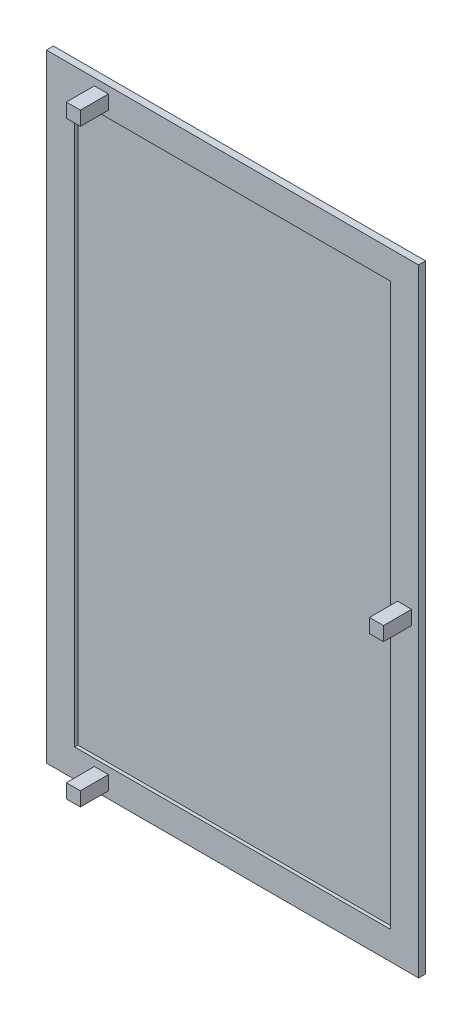
SolidWorks part; units mm, degrees
ref_plane "Front Plane" through (0, 0, 0) normal (0, 0, 1) x (1, 0, 0)
ref_plane "Top Plane" through (0, 0, 0) normal (0, 1, 0) x (1, 0, 0)
ref_plane "Right Plane" through (0, 0, 0) normal (1, 0, 0) x (0, 0, -1)
sketch "Sketch1" plane through (0, 0, 0) normal (0, 0, 1) x (1, 0, 0)
  line L1 (0, 0) -> (66.3, 0)
  line L2 (0, 0) -> (0, 110)
  line L3 (0, 110) -> (66.3, 110)
  line L4 (66.3, 0) -> (66.3, 110)
  dimension "D1" = 110
  dimension "D2" = 66.3
extrude "Boss-Extrude1" add sketch "Sketch1" along normal blind 1.25
sketch "Sketch2" plane through (0, 0, 1.25) normal (0, 0, 1) x (1, 0, 0)
  line L0 (0, 0) -> (66.3, 0) construction
  line L1 (8.55, 1.25) -> (11.05, 1.25)
  line L2 (8.55, 1.25) -> (8.55, 3.75)
  line L3 (8.55, 3.75) -> (11.05, 3.75)
  line L4 (11.05, 1.25) -> (11.05, 3.75)
  line L5 (66.3, 0) -> (66.3, 110) construction
  line L6 (66.3, 110) -> (0, 110) construction
  line L7 (8.55, 108.75) -> (11.05, 108.75)
  line L8 (8.55, 108.75) -> (8.55, 106.25)
  line L9 (8.55, 106.25) -> (11.05, 106.25)
  line L10 (11.05, 108.75) -> (11.05, 106.25)
  line L12 (62.55, 56.25) -> (65.05, 56.25)
  line L13 (62.55, 56.25) -> (62.55, 53.75)
  line L14 (62.55, 53.75) -> (65.05, 53.75)
  line L15 (65.05, 56.25) -> (65.05, 53.75)
  dimension "D1" = 2.5
  dimension "D2" = 2.5
  dimension "D3" = 1.25
  dimension "D4" = 55.25
  dimension "D5" = 2.5
  dimension "D6" = 2.5
  dimension "D7" = 1.25
  dimension "D8" = 55.25
  dimension "D9" = 2.5
  dimension "D10" = 2.5
  dimension "D11" = 1.25
  dimension "D12" = 53.75
extrude "Boss-Extrude2" add sketch "Sketch2" along normal blind 5
sketch "Sketch3" plane through (0, 0, 1.25) normal (0, 0, 1) x (1, 0, 0)
  line L0 (0, 110) -> (0, 0) construction
  line L1 (5, 105) -> (61.3, 105)
  line L2 (5, 105) -> (5, 5)
  line L3 (5, 5) -> (61.3, 5)
  line L4 (61.3, 105) -> (61.3, 5)
  line L5 (66.3, 110) -> (0, 110) construction
  line L6 (66.3, 0) -> (66.3, 110) construction
  line L7 (0, 0) -> (66.3, 0) construction
  dimension "D1" = 5
  dimension "D2" = 5
  dimension "D3" = 5
  dimension "D4" = 5
extrude "Cut-Extrude1" cut sketch "Sketch3" against normal blind 0.6
